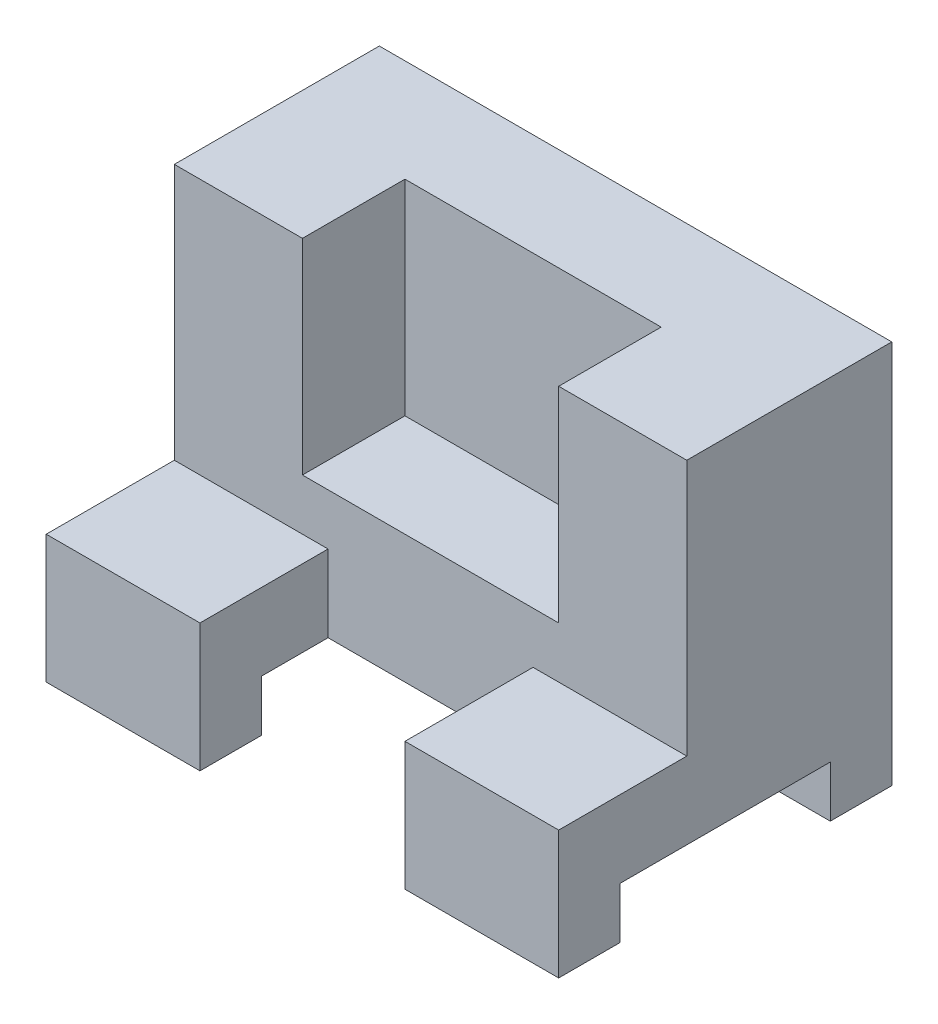
SolidWorks part; units mm, degrees
ref_plane "Front Plane" through (0, 0, 0) normal (0, 0, 1) x (1, 0, 0)
ref_plane "Top Plane" through (0, 0, 0) normal (0, 1, 0) x (1, 0, 0)
ref_plane "Right Plane" through (0, 0, 0) normal (1, 0, 0) x (0, 0, -1)
sketch "Sketch1" plane through (0, 0, 0) normal (0, 0, 1) x (1, 0, 0)
  line L1 (0, 0) -> (100, 0)
  line L2 (0, 0) -> (0, -65)
  line L3 (0, -65) -> (100, -65)
  line L4 (100, 0) -> (100, -65)
  dimension "D1" = 100
  dimension "D2" = 65
extrude "Boss-Extrude1" add sketch "Sketch1" along normal blind 40
sketch "Sketch2" plane through (0, 0, 0) normal (0, 1, 0) x (1, 0, 0)
  line L0 (25, -40) -> (25, -20)
  line L1 (100, -40) -> (0, -40) construction
  line L2 (25, -20) -> (75, -20)
  line L3 (75, -20) -> (75, -40)
  line L4 (75, -40) -> (25, -40)
  line L5 (100, -40) -> (100, 0) construction
  line L6 (0, -40) -> (0, 0) construction
  dimension "D1" = 20
  dimension "D2" = 25
  dimension "D3" = 25
extrude "Cut-Extrude1" cut sketch "Sketch2" against normal blind 40
sketch "Sketch3" plane through (0, 0, 40) normal (0, 0, 1) x (1, 0, 0)
  line L0 (0, -50) -> (0, -75)
  line L3 (0, -50) -> (30, -50)
  line L7 (100, -50) -> (70, -50)
  line L9 (0, -75) -> (-0.1307, -74.8644)
  line L10 (30, -50) -> (30, -75)
  line L11 (30, -75) -> (0, -75)
  line L12 (70, -50) -> (70, -75)
  line L13 (70, -75) -> (100, -75)
  line L14 (100, -75) -> (100, -50)
  line L15 (0, -65) -> (100, -65) construction
  line M13 (0, 0) -> (0, -65)
  line M14 (0, -65) -> (100, -65)
  line M15 (100, -65) -> (100, 0)
  dimension "D1" = 30
  dimension "D2" = 30
  dimension "D3" = 25
  dimension "D4" = 25
  dimension "D5" = 10
  dimension "D6" = 10
extrude "Boss-Extrude2" add sketch "Sketch3" along normal blind 25 contours L10 L3 M13 M14 | L7 L12 M14 M15 | L11 L10 L0 M14 | L13 L14 L12 M14
sketch "Sketch4" plane through (0, -65, 0) normal (0, -1, 0) x (1, 0, 0)
  line L0 (100, 40) -> (100, 0) construction
  line L1 (0, 0) -> (100, 0)
  line L2 (0, 0) -> (0, 12)
  line L3 (0, 12) -> (100, 12)
  line L4 (100, 0) -> (100, 12)
  dimension "D1" = 12
extrude "Boss-Extrude3" add sketch "Sketch4" along normal blind 10
sketch "Sketch5" plane through (100, 0, 0) normal (1, 0, 0) x (0, 0, -1)
  line L0 (-65, -75) -> (-65, -50) construction
  line L1 (-40, -75) -> (-53, -75)
  line L2 (-40, -75) -> (-40, -65)
  line L3 (-40, -65) -> (-53, -65)
  line L4 (-53, -75) -> (-53, -65)
  dimension "D1" = 12
  dimension "D2" = 10
extrude "Cut-Extrude2" cut sketch "Sketch5" against normal through all
